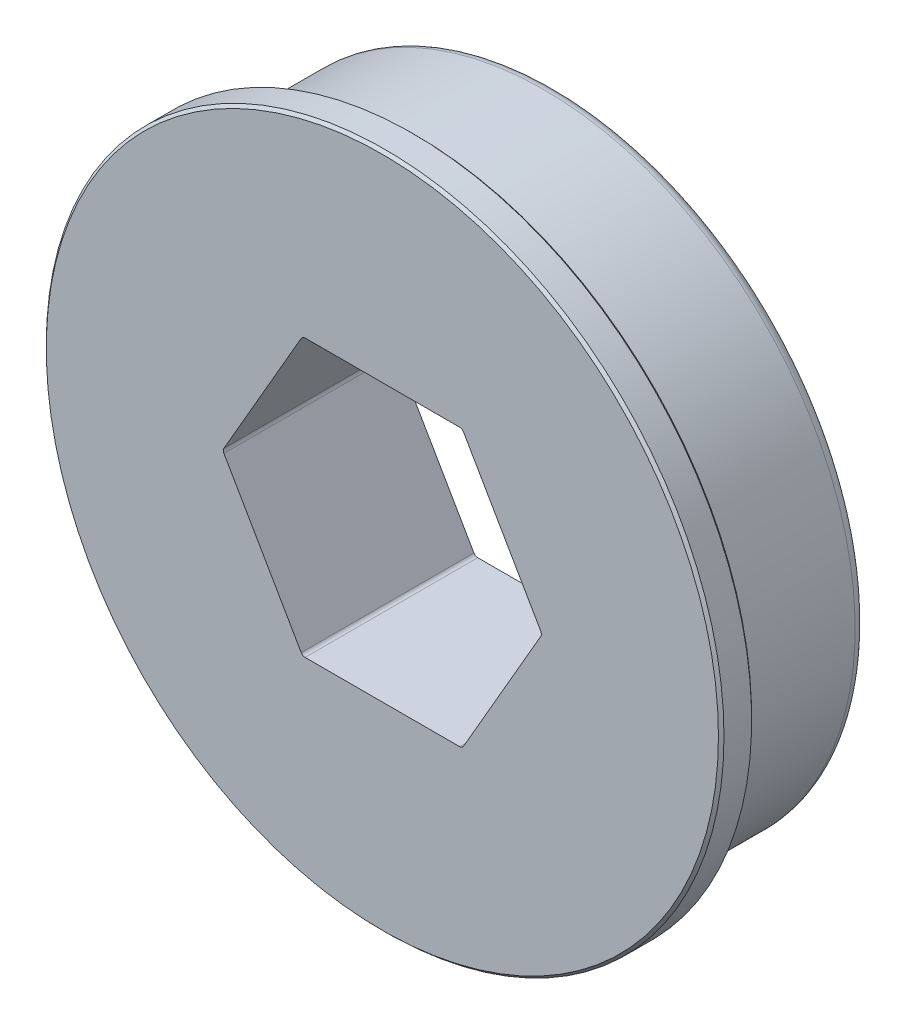
SolidWorks part; units mm, degrees
material "AISI 1020"
ref_plane "Front Plane" through (0, 0, 0) normal (0, 0, 1) x (1, 0, 0)
ref_plane "Top Plane" through (0, 0, 0) normal (0, 1, 0) x (1, 0, 0)
ref_plane "Right Plane" through (0, 0, 0) normal (1, 0, 0) x (0, 0, -1)
ref_plane "Plane1" through (0, 0, 0) normal (0, -1, 0) x (1, 0, 0)
sketch "Sketch1" plane through (0, 0, 0) normal (0, -1, 0) x (1, 0, 0)
  line L0 (15.5575, 7.9273) -> (0, 7.9273)
  line L1 (0, 7.9273) -> (0, 0)
  line L2 (0, 0) -> (14.2875, 0)
  line L3 (14.2875, 0) -> (14.2875, 5.8953)
  line L4 (14.2875, 5.8953) -> (13.97, 5.8953)
  line L5 (13.97, 5.8953) -> (13.97, 6.4033)
  line L6 (13.97, 6.4033) -> (15.5575, 6.4033)
  line L7 (15.5575, 6.4033) -> (15.5575, 7.9273)
  line L8 (0, 7.9273) -> (0, 0) construction
revolve "Revolve1" add sketch "Sketch1" angle 360 about L8
sketch "Sketch2" plane through (0, 0, 0) normal (0, 0, -1) x (-1, 0, 0)
  line L0 (3.6662, 6.35) -> (-3.6662, 6.35)
  line L1 (-3.6662, 6.35) -> (-7.3323, 0)
  line L2 (-7.3323, 0) -> (-3.6662, -6.35)
  line L3 (-3.6662, -6.35) -> (3.6662, -6.35)
  line L4 (3.6662, -6.35) -> (7.3323, 0)
  line L5 (7.3323, 0) -> (3.6662, 6.35)
extrude "Cut-Extrude1" cut sketch "Sketch2" against normal through all
chamfer "Chamfer1" distance 0.127 angle 45 2 edges at (-15.5575, 0, 7.9273) (-15.5575, 0, 6.4033)
fillet "Fillet1" radius 0.2032 6 edges at (-3.6662, -6.35, 3.9637) (7.3323, 0, 3.9637) (-7.3323, 0, 3.9637) (-3.6662, 6.35, 3.9637) (3.6662, -6.35, 3.9637) (3.6662, 6.35, 3.9637)
fillet "Fillet2" radius 0.508 1 edges at (-14.2875, 0, 0)
